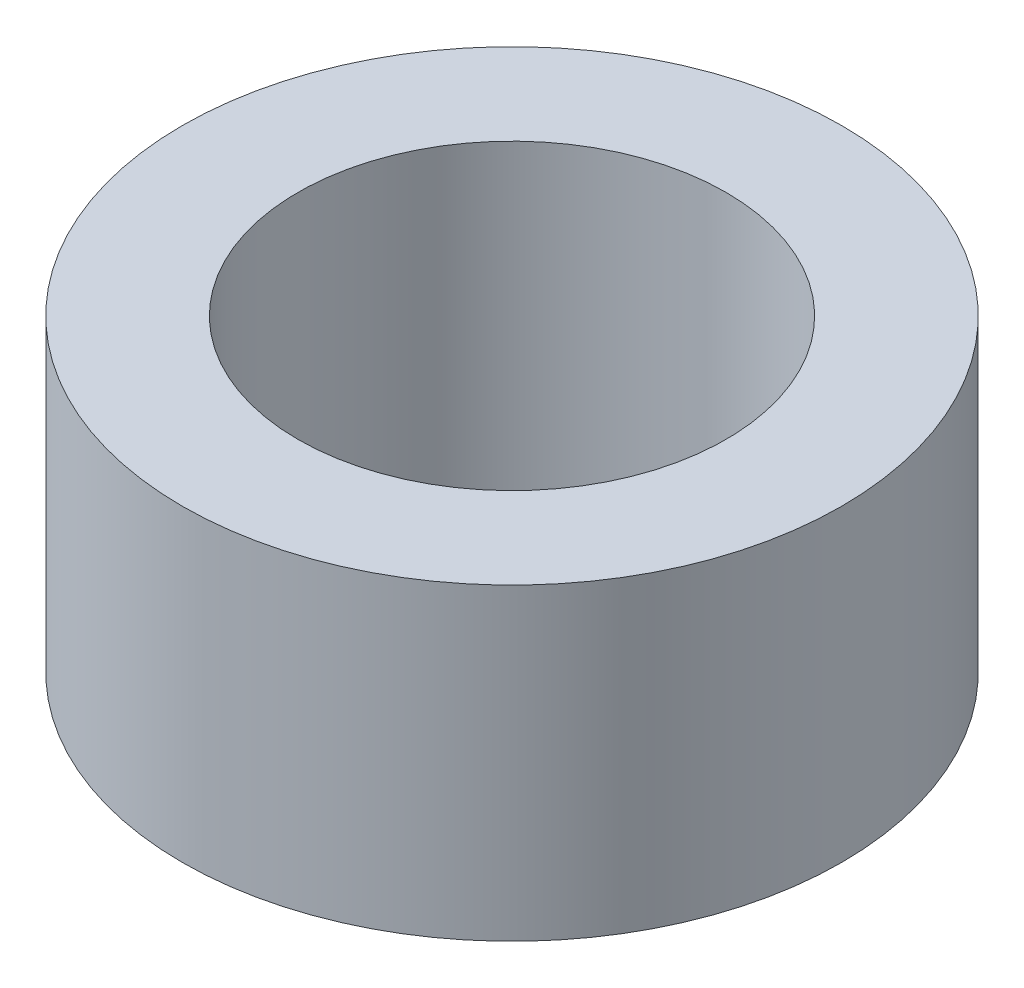
SolidWorks part; units mm, degrees
ref_plane "Front Plane" through (0, 0, 0) normal (0, 0, 1) x (1, 0, 0)
ref_plane "Top Plane" through (0, 0, 0) normal (0, 1, 0) x (1, 0, 0)
ref_plane "Right Plane" through (0, 0, 0) normal (1, 0, 0) x (0, 0, -1)
sketch "Sketch1" plane through (0, 0, 0) normal (0, 1, 0) x (1, 0, 0)
  circle A0 centre (0, 0) radius 2.775
  circle A1 centre (0, 0) radius 4.275
  dimension "D1" = 5.55
  dimension "D2" = 1.5
extrude "Boss-Extrude1" add sketch "Sketch1" along normal blind 4
